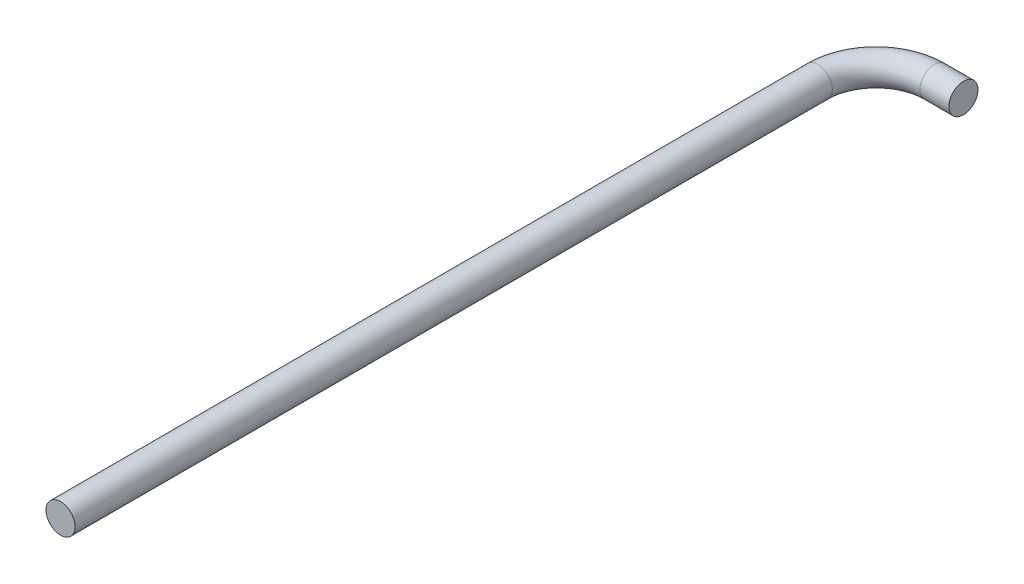
SolidWorks part; units mm, degrees
ref_plane "Plan de face" through (0, 0, 0) normal (0, 0, 1) x (1, 0, 0)
ref_plane "Plan de dessus" through (0, 0, 0) normal (0, 1, 0) x (1, 0, 0)
ref_plane "Plan de droite" through (0, 0, 0) normal (1, 0, 0) x (0, 0, -1)
sketch "Esquisse1" plane through (0, 0, 0) normal (0, 0, 1) x (1, 0, 0)
  line L0 (0, 7.9563) -> (0, -9.2097)
  circle A0 centre (-10, 0) radius 2.5
  dimension "D2" = 5
  dimension "D1" = 10
revolve "Révolution1" add sketch "Esquisse1" angle 90 about L0
sketch "Esquisse2" plane through (0, 0, 0) normal (0, 0, 1) x (1, 0, 0)
  circle A0 centre (-10, 0) radius 2.5
extrude "Boss.-Extru.1" add sketch "Esquisse2" along normal blind 130
sketch "Esquisse3" plane through (0, 0, 0) normal (1, 0, 0) x (0, 0, -1)
  circle A0 centre (10, 0) radius 2.5
extrude "Boss.-Extru.2" add sketch "Esquisse3" along normal blind 5
